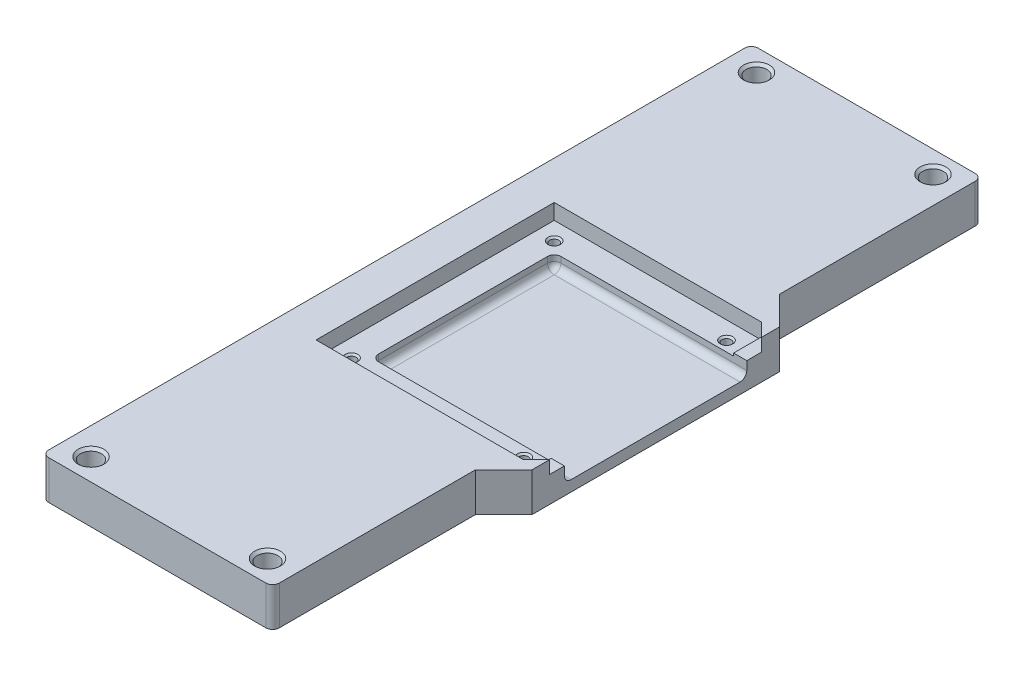
SolidWorks part; units mm, degrees
ref_plane "Front Plane" through (0, 0, 0) normal (0, 0, 1) x (1, 0, 0)
ref_plane "Top Plane" through (0, 0, 0) normal (0, 1, 0) x (1, 0, 0)
ref_plane "Right Plane" through (0, 0, 0) normal (1, 0, 0) x (0, 0, -1)
sketch "Sketch1" plane through (0, 0, 0) normal (0, 1, 0) x (1, 0, 0)
  line L0 (0, -90) -> (0, 90) construction
  line L1 (34.125, 90) -> (-34.125, 90) construction
  line L2 (-34.125, 90) -> (-34.125, -90)
  line L3 (-34.125, 0) -> (34.125, 0) construction
  line L4 (-34.125, 90) -> (-34.125, 103)
  line L5 (-32.125, 105) -> (32.125, 105)
  line L6 (0, 105) -> (0, 90) construction
  line L7 (34.125, 90) -> (34.125, 103)
  line L8 (34.125, 90) -> (34.125, -90)
  line L9 (0, -105) -> (0, -90) construction
  line L10 (34.125, -90) -> (-34.125, -90) construction
  line L11 (34.125, -90) -> (34.125, -103)
  line L12 (-32.125, -105) -> (32.125, -105)
  line L13 (-34.125, -90) -> (-34.125, -103)
  line L14 (-34.125, 93) -> (34.125, 93) construction
  circle A1 centre (-26.125, 98.5) radius 3.075 construction
  circle A2 centre (26.125, 98.5) radius 3.075 construction
  circle A5 centre (26.125, -98.5) radius 3.075 construction
  circle A6 centre (-26.125, -98.5) radius 3.075 construction
  arc A8 (-32.125, -105) -> (-34.125, -103) centre (-32.125, -103) cw
  arc A9 (34.125, -103) -> (32.125, -105) centre (32.125, -103) cw
  arc A10 (34.125, 103) -> (32.125, 105) centre (32.125, 103) ccw
  arc A11 (-34.125, 103) -> (-32.125, 105) centre (-32.125, 103) cw
  point P24 (0, 0)
  point P36 (-34.125, -105)
  point P39 (34.125, -105)
  point P42 (34.125, 105)
  point P45 (-34.125, 105)
  dimension "D10" = 2
  dimension "D3" = 6.15
  dimension "D1" = 34.125
  dimension "D2" = 90
  dimension "D4" = 6.5
  dimension "D6" = 8
  dimension "D7" = 8.5
  dimension "D8" = 12
  dimension "D9" = 3
  dimension "D11" = 105
extrude "Boss-Extrude1" add sketch "Sketch1" along normal blind 11.5
sketch "Sketch3" plane through (0, 11.5, 0) normal (0, 1, 0) x (1, 0, 0)
  line L0 (0, 0) -> (-34.125, 0) construction
  line L1 (-34.125, 103) -> (-34.125, -103) construction
  line L2 (0, 0) -> (0, 105) construction
  line L3 (32.125, 105) -> (-32.125, 105) construction
  line L4 (3.96, -16.3) -> (3.96, 16.3)
  line L5 (-2.46, -17.8) -> (2.46, -17.8)
  line L6 (-3.96, 16.3) -> (-3.96, -16.3)
  line L7 (2.46, 17.8) -> (-2.46, 17.8)
  line L8 (0, 17.8) -> (0, -17.8) construction
  line L9 (13.25, 0) -> (0, 0) construction
  line L10 (16.15, 10.025) -> (10.35, 10.025)
  line L11 (16.15, 10.025) -> (16.15, -10.025)
  line L12 (16.15, -10.025) -> (10.35, -10.025)
  line L13 (10.35, 10.025) -> (10.35, -10.025)
  line L14 (16.15, 10.025) -> (10.35, -10.025) construction
  line L15 (16.15, -10.025) -> (10.35, 10.025) construction
  line L16 (13.25, 0) -> (13.25, 10.025) construction
  line L17 (-16.15, 10.025) -> (-16.15, -10.025)
  line L18 (-16.15, -10.025) -> (-10.35, -10.025)
  line L23 (-16.15, 10.025) -> (-10.35, 10.025)
  line L24 (-10.35, 10.025) -> (-10.35, -10.025)
  arc A0 (-2.46, 17.8) -> (-3.96, 16.3) centre (-2.46, 16.3) ccw
  arc A1 (3.96, 16.3) -> (2.46, 17.8) centre (2.46, 16.3) ccw
  arc A2 (2.46, -17.8) -> (3.96, -16.3) centre (2.46, -16.3) ccw
  arc A3 (-3.96, -16.3) -> (-2.46, -17.8) centre (-2.46, -16.3) ccw
  point P9 (0, 0)
  point P23 (0, 0)
  dimension "D2" = 1.5
  dimension "D1" = 35.6
  dimension "D3" = 7.92
  dimension "D4" = 20.05
  dimension "D5" = 5.8
  dimension "D6" = 13.25
sketch "Sketch4" plane through (0, 11.5, 0) normal (0, 1, 0) x (1, 0, 0)
  circle A0 centre (-26.125, -98.5) radius 3.075 construction
  circle A1 centre (26.125, -98.5) radius 3.075 construction
  circle A2 centre (26.125, 98.5) radius 3.075 construction
  circle A5 centre (-26.125, 98.5) radius 3.075 construction
  circle A8 centre (-26.125, -98.5) radius 3.075
  circle A9 centre (26.125, -98.5) radius 3.075
  circle A10 centre (26.125, 98.5) radius 3.075
  circle A13 centre (-26.125, 98.5) radius 3.075
extrude "Cut-Extrude1" cut sketch "Sketch4" against normal blind 6
sketch "Sketch27" plane through (0, 11.5, 0) normal (0, 1, 0) x (1, 0, 0)
  line L0 (38.5, 35) -> (-22.5, 35) construction
  line L1 (34.125, 45) -> (42.5, 36.625)
  line L2 (-22.5, 35) -> (-22.5, -35) construction
  line L3 (-22.5, 0) -> (0, 0) construction
  line L4 (38.5, -35) -> (38.5, 35) construction
  line L5 (38.5, -35) -> (-22.5, -35) construction
  line L7 (0, 0) -> (38.5, 0) construction
  line L8 (34.125, -103) -> (34.125, 103) construction
  line L9 (42.5, 36.625) -> (42.5, -36.625)
  line L10 (42.5, 0) -> (38.5, 0) construction
  line L11 (34.125, 45) -> (34.125, -45)
  line L12 (34.125, 0) -> (42.5, 0) construction
  line L13 (34.125, -45) -> (42.5, -36.625)
  circle A0 centre (-17.5, 30) radius 1.6 construction
  circle A1 centre (33.5, 30) radius 1.6 construction
  circle A2 centre (33.5, -30) radius 1.6 construction
  circle A3 centre (-17.5, -30) radius 1.6 construction
  dimension "D8" = 3.2
  dimension "D1" = 22.5
  dimension "D2" = 61
  dimension "D3" = 35
  dimension "D4" = 5
  dimension "D5" = 5
  dimension "D6" = 5
  dimension "D7" = 5
  dimension "D9" = 45
  dimension "D10" = 4
  dimension "D11" = 10
extrude "Boss-Extrude3" add sketch "Sketch27" against normal up to surface (11.5 mm away) up to face at (0, 0, 0)
sketch "Sketch21" plane through (0, 11.5, 0) normal (0, 1, 0) x (1, 0, 0)
  line L0 (38.5, 35) -> (-22.5, 35) construction
  line L1 (38.5, 35) -> (42.5, 31) construction
  line L2 (-22.5, 35) -> (-22.5, -35) construction
  line L3 (-22.5, 0) -> (0, 0) construction
  line L5 (38.5, -35) -> (38.5, 35) construction
  line L6 (38.5, -35) -> (-22.5, -35) construction
  line L7 (42.5, 31) -> (42.5, 31.3536) construction
  line L10 (0, 0) -> (38.5, 0) construction
  line L11 (42.5, 31.3536) -> (42.5, -31.3536)
  line L14 (38.6036, 35.25) -> (42.5, 31.3536)
  line L15 (38.6036, 35.25) -> (-22.75, 35.25)
  line L16 (-22.75, 35.25) -> (-22.75, -35.25)
  line L17 (38.6036, -35.25) -> (-22.75, -35.25)
  line L22 (41.1909, -32.6626) -> (40.4837, -33.8199) construction
  line L23 (42.5, 31.3536) -> (43.8534, 32.707) construction
  line L24 (42.5, -31) -> (40.697, -33.9503) construction
  line L25 (42.5, 31) -> (44.0302, 32.5302) construction
  line L26 (38.6036, -35.25) -> (41.1909, -32.6626) construction
  line L27 (38.5, -35) -> (42.5, -31) construction
  line L29 (42.5, 0) -> (38.5, 0) construction
  line L30 (42.5, -36.625) -> (42.5, 36.625) construction
  line L31 (38.6036, -35.25) -> (42.5, -31.3536)
  circle A0 centre (-17.5, 30) radius 1.6 construction
  circle A1 centre (33.5, 30) radius 1.6 construction
  circle A2 centre (33.5, -30) radius 1.6 construction
  circle A3 centre (-17.5, -30) radius 1.6 construction
  point P2 (-123.1318, 54.1866)
  point P19 (42.5, 0)
  dimension "D8" = 3.2
  dimension "D1" = 22.5
  dimension "D2" = 61
  dimension "D3" = 35
  dimension "D4" = 5
  dimension "D5" = 5
  dimension "D6" = 5
  dimension "D7" = 5
  dimension "D9" = 45
  dimension "D10" = 4
  dimension "D11" = 0.25
extrude "Cut-Extrude6" cut sketch "Sketch21" against normal blind 4.6
sketch "Sketch24" plane through (0, 6.9, 0) normal (0, 1, 0) x (1, 0, 0)
  line L0 (42.5, 27) -> (-14.5, 27)
  line L1 (42.5, -31.3536) -> (42.5, 31.3536) construction
  line L2 (-14.5, 27) -> (-14.5, -27)
  line L3 (-14.5, -27) -> (42.5, -27)
  line L4 (42.5, -27) -> (42.5, 27)
  line L8 (38.5, 35) -> (-22.5, 35) construction
  line L10 (-22.5, 35) -> (-22.5, -35) construction
  line L11 (38.5, -35) -> (-22.5, -35) construction
  point P2 (0, 0)
  point P3 (42.5, -27)
  dimension "D1" = 8
  dimension "D2" = 8
  dimension "D3" = 8
extrude "Cut-Extrude3" cut sketch "Sketch24" against normal blind 3.7 and the other way through all
sketch "Sketch25" plane through (0, 6.9, 0) normal (0, 1, 0) x (1, 0, 0)
  circle A0 centre (33.5, 30) radius 1.35
  circle A1 centre (-17.5, 30) radius 1.35
  circle A2 centre (33.5, -30) radius 1.35
  circle A3 centre (-17.5, -30) radius 1.35
  dimension "D1" = 2.7
extrude "Cut-Extrude4" cut sketch "Sketch25" against normal blind 5
chamfer "Chamfer4" distance 0.5 angle 45 4 edges at (-17.5, 6.9, 31.35) (33.5, 6.9, 31.35) (33.5, 6.9, -28.65) (-17.5, 6.9, -28.65)
fillet "Fillet1" radius 2 5 edges at (14, 3.2, 27) (-14.5, 5.05, 27) (-14.5, 5.05, -27) (-14.5, 3.2, 0) (14, 3.2, -27)
sketch "Sketch26" plane through (0, 6.9, 0) normal (0, 1, 0) x (1, 0, 0)
  line L0 (0, 0) -> (34.125, 0) construction
  line L1 (34.125, -25) -> (34.125, 25) construction
  line L2 (38.6036, 35.25) -> (38.6036, 27)
  line L3 (42.5, 27) -> (-12.5, 27) construction
  line L4 (38.6036, 27) -> (42.5, 27)
  line L5 (42.5, 27) -> (42.5, 31.3536)
  line L7 (42.5, 31.3536) -> (38.6036, 35.25)
  line L8 (42.5, -31.3536) -> (38.6036, -35.25)
  line L11 (38.6036, -27) -> (42.5, -27)
  line L12 (38.6036, -35.25) -> (38.6036, -27)
  line L13 (42.5, 27) -> (42.5, 31.3536) construction
  line L14 (42.5, -31.3536) -> (42.5, -27)
extrude "Boss-Extrude2" add sketch "Sketch26" along normal blind 0.8
chamfer "Chamfer5" distance 0.75 angle 45 4 edges at (-26.125, 11.5, 101.575) (26.125, 11.5, 101.575) (26.125, 11.5, -95.425) (-26.125, 11.5, -95.425)
equation "\"D5@Sketch21\"=\"D4@Sketch21\""
equation "\"D6@Sketch21\"=\"D4@Sketch21\""
equation "\"D7@Sketch21\"=\"D4@Sketch21\""
equation "\"D2@Sketch24\"=\"D1@Sketch24\""
equation "\"D3@Sketch24\"=\"D1@Sketch24\""
